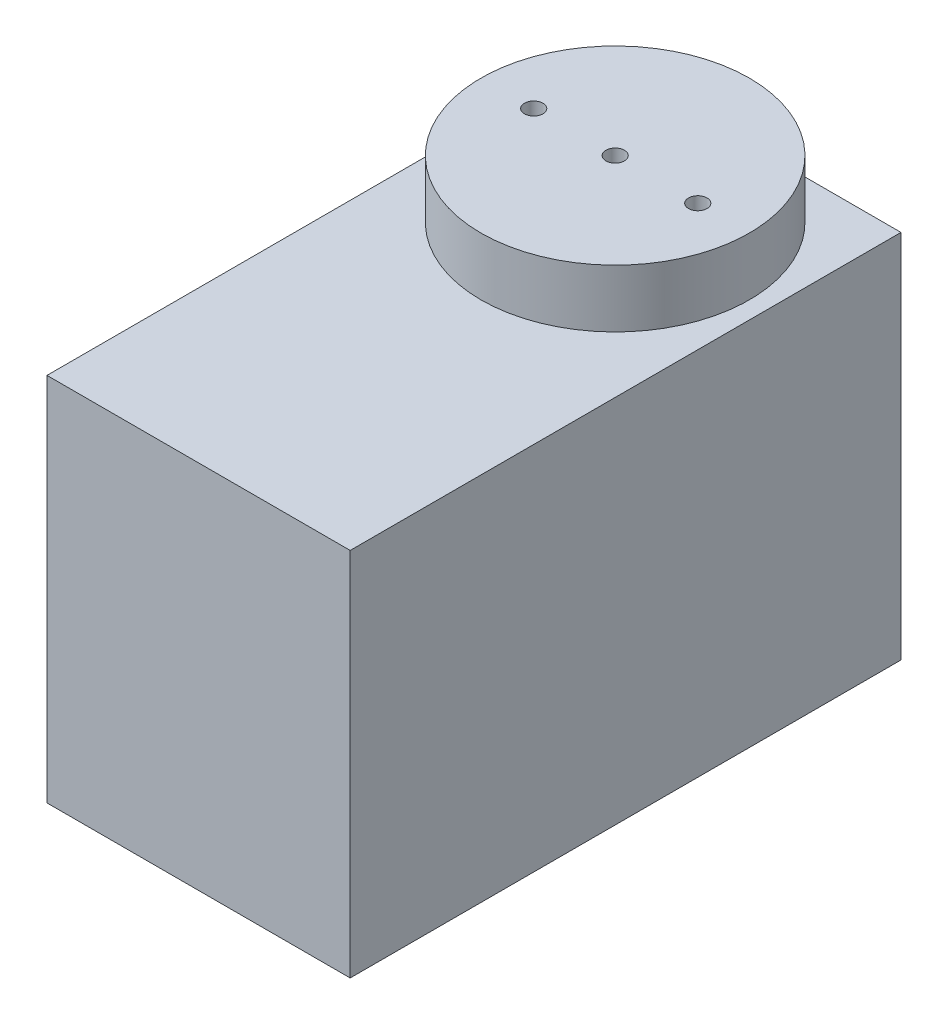
SolidWorks part; units mm, degrees
material "PBT General Purpose"
ref_plane "Front Plane" through (0, 0, 0) normal (0, 0, 1) x (1, 0, 0)
ref_plane "Top Plane" through (0, 0, 0) normal (0, 1, 0) x (1, 0, 0)
ref_plane "Right Plane" through (0, 0, 0) normal (1, 0, 0) x (0, 0, -1)
sketch "Sketch1" plane through (0, 0, 0) normal (0, 1, 0) x (1, 0, 0)
  line L1 (-13.1, -23.8) -> (13.1, -23.8)
  line L2 (-13.1, -23.8) -> (-13.1, 23.8)
  line L3 (-13.1, 23.8) -> (13.1, 23.8)
  line L4 (13.1, -23.8) -> (13.1, 23.8)
  line L5 (-13.1, -23.8) -> (13.1, 23.8) construction
  line L6 (-13.1, 23.8) -> (13.1, -23.8) construction
  point P0 (0, 0)
  dimension "D1" = 26.2
  dimension "D2" = 47.6
extrude "Boss-Extrude1" add sketch "Sketch1" along normal blind 32
sketch "Sketch2" plane through (0, 32, 0) normal (0, 1, 0) x (-1, 0, 0)
  circle A0 centre (0, -12.2) radius 11.6
  point P2 (0, -23.8)
  dimension "D1" = 11.6
extrude "Boss-Extrude2" add sketch "Sketch2" along normal blind 5
ref_point "Point1"
hole_wizard "M2x0.4 Tapped Hole1" positions "3DSketch1" profile "Sketch4" tap size "M2x0.4" standard "Ansi Metric"
sketch3d "3DSketch1"
  line L0 (0, 37, -12.2) -> (0, 32, -12.2) construction
  line L1 (0, 37, -12.2) -> (-7.0399, 37, -12.2) construction
  line L3 (0, 37, -12.2) -> (7.1368, 37, -12.2) construction
  point P0 (0, 37, -12.2)
  point P4 (-7.0399, 37, -12.2)
  point P10 (7.1368, 37, -12.2)
sketch "Sketch4" plane through (0, 37, -12.2) normal (1, 0, 0) x (0, 0, 1)
  line L0 (0, 0) -> (0, 5.6807)
  line L1 (0, 5.6807) -> (0.8, 5.2)
  line L2 (0.8, 5.2) -> (0.8, 0)
  line L5 (0.8, 0) -> (0, 0)
  line L10 (0, 5.6807) -> (-0.8, 5.2) construction
  line L11 (0, -6.35) -> (0, 107.95) construction
  dimension "Tap Drill Dia." = 1.6
  dimension "Tap Drill Depth" = 5.2
  dimension "Drill Angle" = 118
cosmetic thread "Hole Thread1" parameters "D1"=4, "D2"=2
cosmetic thread "Hole Thread2" parameters "D1"=4, "D2"=2
cosmetic thread "Hole Thread3" parameters "D1"=4, "D2"=2
